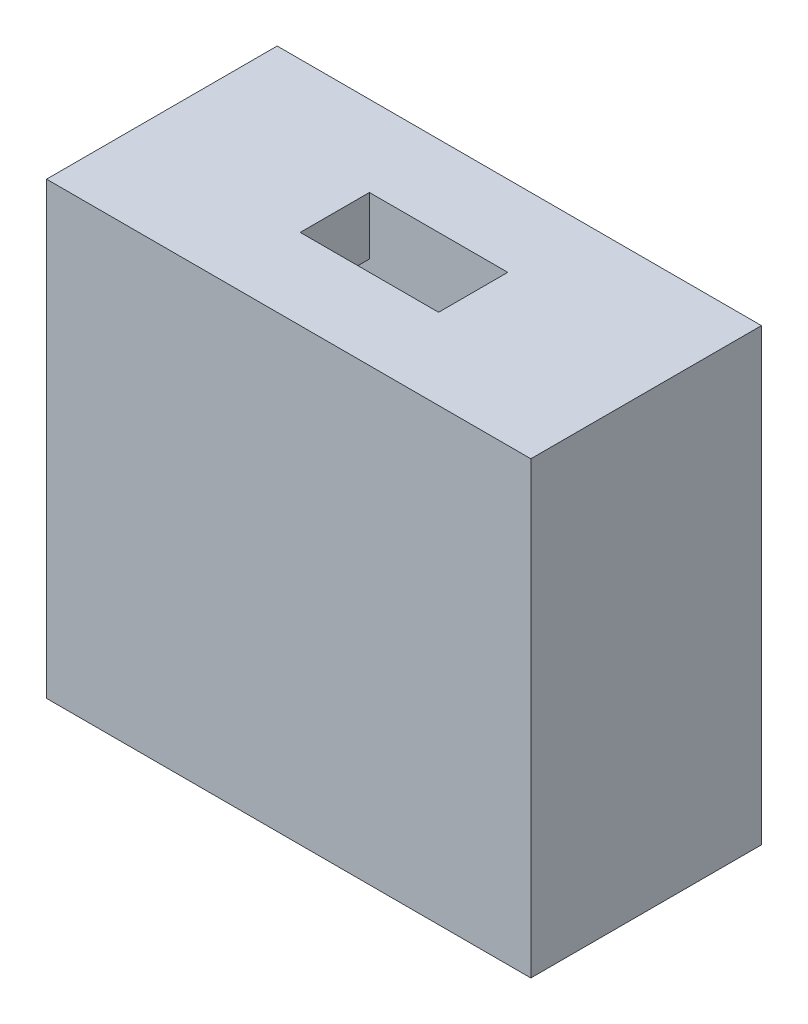
SolidWorks part; units mm, degrees
ref_plane "Plan de face" through (0, 0, 0) normal (0, 0, 1) x (1, 0, 0)
ref_plane "Plan de dessus" through (0, 0, 0) normal (0, 1, 0) x (1, 0, 0)
ref_plane "Plan de droite" through (0, 0, 0) normal (1, 0, 0) x (0, 0, -1)
sketch "Esquisse1" plane through (0, 0, 0) normal (0, 1, 0) x (1, 0, 0)
  line L1 (-21, 10) -> (21, 10)
  line L2 (-21, 10) -> (-21, -10)
  line L3 (-21, -10) -> (21, -10)
  line L4 (21, 10) -> (21, -10)
  line L5 (-21, 10) -> (21, -10) construction
  line L6 (-21, -10) -> (21, 10) construction
  point P0 (0, 0)
  dimension "D1" = 42
  dimension "D2" = 20
extrude "Boss.-Extru.1" add sketch "Esquisse1" along normal blind 39
sketch "Esquisse2" plane through (0, 39, 0) normal (0, 1, 0) x (1, 0, 0)
  line L1 (-6, -3) -> (6, -3)
  line L2 (-6, -3) -> (-6, 3)
  line L3 (-6, 3) -> (6, 3)
  line L4 (6, -3) -> (6, 3)
  line L5 (-6, -3) -> (6, 3) construction
  line L6 (-6, 3) -> (6, -3) construction
  point P0 (0, 0)
  dimension "D1" = 12
  dimension "D2" = 6
extrude "Enlèv. mat.-Extru.1" cut sketch "Esquisse2" against normal blind 10
sketch "Esquisse3" plane through (-6, 0, 0) normal (1, 0, 0) x (0, 0, -1)
  line L0 (3, 29) -> (3, 39) construction
  line L1 (-3, 29) -> (3, 29)
  line L2 (-3, 29) -> (-3, 34)
  line L3 (-3, 34) -> (3, 34)
  line L4 (3, 29) -> (3, 34)
extrude "Enlèv. mat.-Extru.2" cut sketch "Esquisse3" against normal through all
